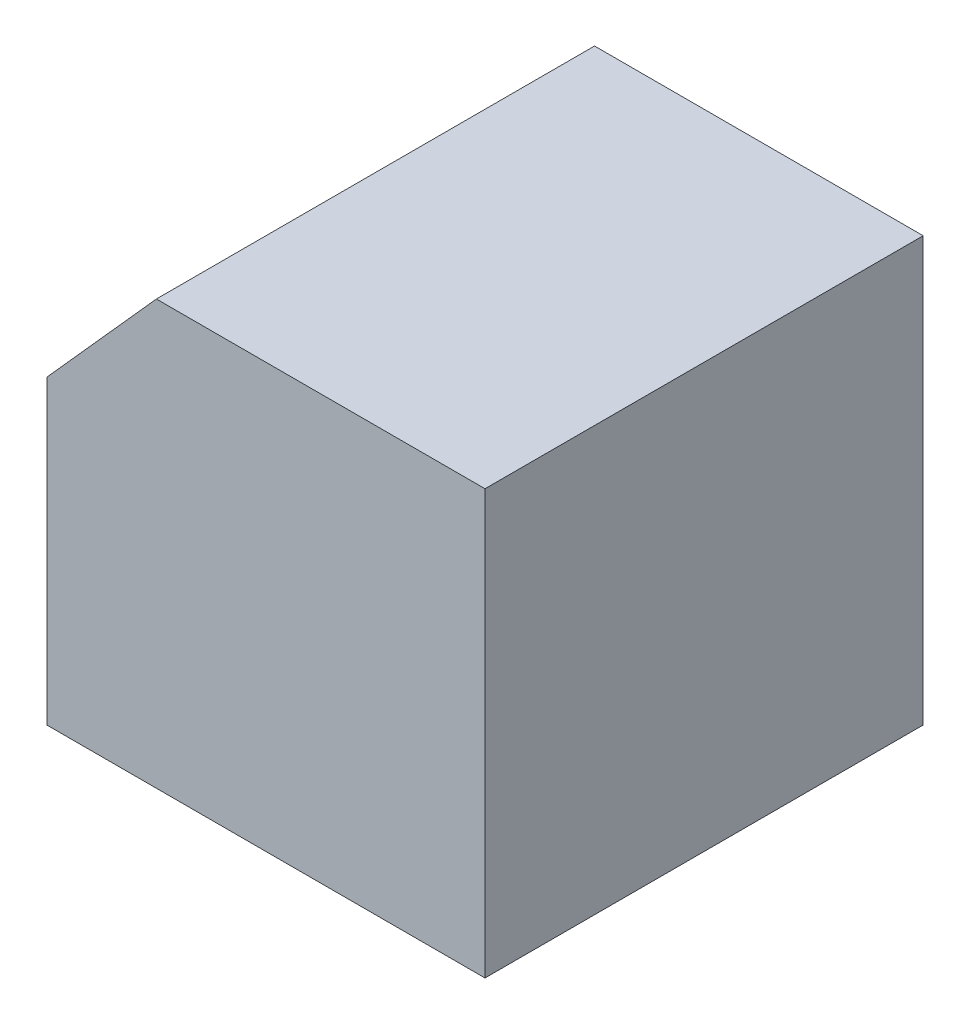
SolidWorks part; units mm, degrees
ref_plane "Front Plane" through (0, 0, 0) normal (0, 0, 1) x (1, 0, 0)
ref_plane "Top Plane" through (0, 0, 0) normal (0, 1, 0) x (1, 0, 0)
ref_plane "Right Plane" through (0, 0, 0) normal (1, 0, 0) x (0, 0, -1)
sketch "Sketch1" plane through (0, 0, 0) normal (0, 0, 1) x (1, 0, 0)
  line L0 (0, 279.4) -> (0, 0)
  line L1 (0, 0) -> (406.4, 0)
  line L2 (406.4, 0) -> (406.4, 392.9923)
  line L3 (406.4, 392.9923) -> (101.6, 392.9923)
  line L4 (101.6, 392.9923) -> (0, 279.4)
  dimension "D1" = 304.8
  dimension "D2" = 152.4
  dimension "D3" = 406.4
  dimension "D4" = 279.4
extrude "Boss-Extrude1" add sketch "Sketch1" along normal blind 406.4
